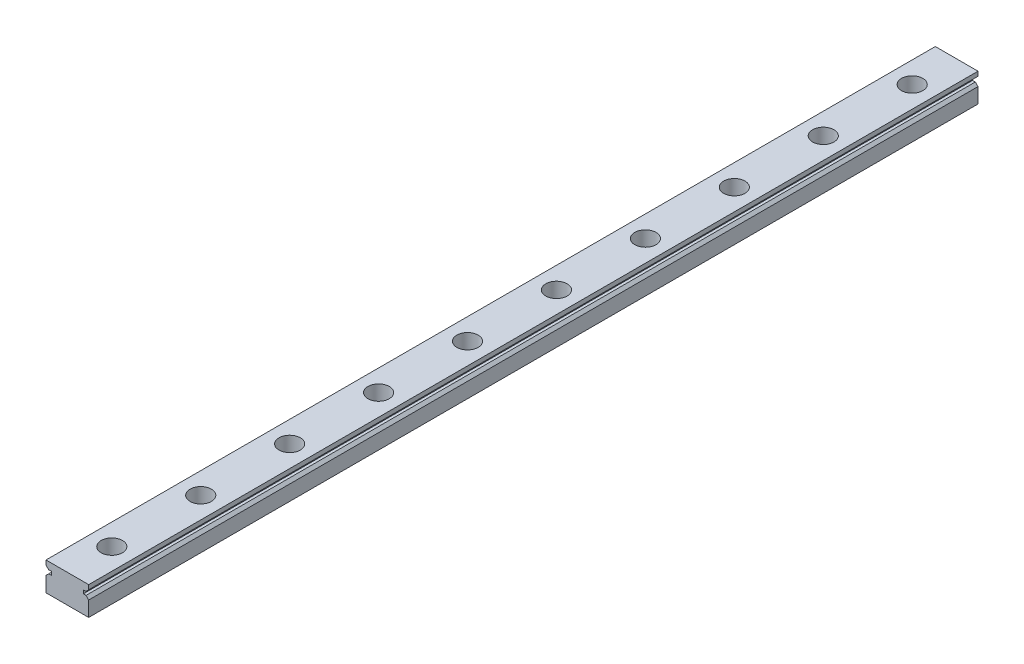
SolidWorks part; units mm, degrees
ref_plane "Front Plane" through (0, 0, 0) normal (0, 0, 1) x (1, 0, 0)
ref_plane "Top Plane" through (0, 0, 0) normal (0, 1, 0) x (1, 0, 0)
ref_plane "Right Plane" through (0, 0, 0) normal (1, 0, 0) x (0, 0, -1)
sketch "Sketch1" plane through (0, 0, 0) normal (0, 0, 1) x (1, 0, 0)
  line L0 (-6, 0) -> (6, 0)
  line L1 (6, 0) -> (6, 4.25)
  line L2 (6, 4.25) -> (5.25, 5)
  line L3 (5.25, 5) -> (4.5, 5)
  line L4 (4.5, 5) -> (4.5, 6)
  line L5 (4.5, 6) -> (5.25, 6)
  line L6 (5.25, 6) -> (6, 6.75)
  line L7 (6, 6.75) -> (6, 8)
  line L8 (6, 8) -> (-6, 8)
  line L9 (0, 0) -> (0, 8) construction
  line L10 (-6, 6.75) -> (-6, 8)
  line L11 (-5.25, 6) -> (-6, 6.75)
  line L12 (-4.5, 6) -> (-5.25, 6)
  line L13 (-4.5, 5) -> (-4.5, 6)
  line L14 (-5.25, 5) -> (-4.5, 5)
  line L15 (-6, 4.25) -> (-5.25, 5)
  line L16 (-6, 0) -> (-6, 4.25)
  point P4 (0, 0)
  point P15 (0, 0)
  point P16 (5.25, 4.6522)
  dimension "D1" = 8
  dimension "D2" = 12
  dimension "D3" = 1
  dimension "D4" = 1.5
  dimension "D5" = 0.75
  dimension "D6" = 225
  dimension "D7" = 2
extrude "Boss-Extrude1" add sketch "Sketch1" along normal blind 250
sketch "Sketch2" plane through (0, 0, 0) normal (1, 0, 0) x (0, 0, -1)
  line L0 (-12.5, 0) -> (-12.5, 8) construction
  line L1 (-14.25, 0) -> (-10.75, 0) construction
  line L2 (-10.75, 0) -> (-10.75, 3.5)
  line L3 (-10.75, 3.5) -> (-9.5, 3.5)
  line L4 (-9.5, 3.5) -> (-9.5, 8)
  line L5 (-15.5, 8) -> (-9.5, 8) construction
  line L7 (-250, 0) -> (0, 0) construction
  line L8 (-250, 8) -> (0, 8) construction
  line L9 (-12.5, 8) -> (0, 8) construction
  line L10 (-12.5, 8) -> (-9.5, 8)
  line L11 (-12.5, 0) -> (-10.75, 0)
  line L12 (-12.5, 0) -> (-12.5, 8)
  point P5 (-12.5, 0)
  point P11 (-12.5, 8)
  dimension "D1" = 6
  dimension "D2" = 3.5
  dimension "D3" = 4.5
  dimension "D4" = 12.5
revolve "Cut-Revolve3" cut sketch "Sketch2" angle 360 about L12
pattern_linear "LPattern1" count 10 spacing 25 along (0, 0, 1) of "Cut-Revolve3"
